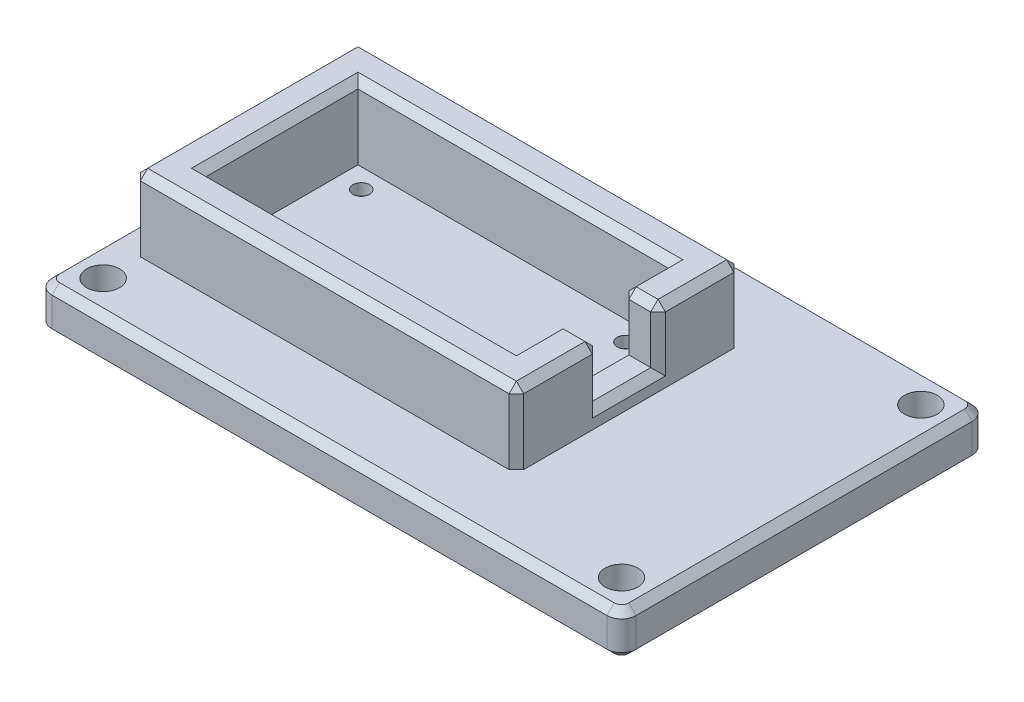
SolidWorks part; units mm, degrees
ref_plane "Front Plane" through (0, 0, 0) normal (0, 0, 1) x (1, 0, 0)
ref_plane "Top Plane" through (0, 0, 0) normal (0, 1, 0) x (1, 0, 0)
ref_plane "Right Plane" through (0, 0, 0) normal (1, 0, 0) x (0, 0, -1)
sketch "Sketch1" plane through (0, 0, 0) normal (0, 1, 0) x (1, 0, 0)
  line L0 (-57.9633, 0) -> (84.3183, 0) construction
  line L1 (-40, 25) -> (40, 25)
  line L2 (-40, 25) -> (-40, -25)
  line L3 (-40, -25) -> (40, -25)
  line L4 (40, 25) -> (40, -25)
  line L5 (-40, 25) -> (40, -25) construction
  line L6 (-40, -25) -> (40, 25) construction
  line L7 (0, 63.2039) -> (0, -51.9764) construction
  dimension "D2" = 50
  dimension "D3" = 80
extrude "Boss-Extrude1" add sketch "Sketch1" along normal blind 6
sketch "Sketch4" plane through (0, 6, 0) normal (0, 1, 0) x (1, 0, 0)
  line L0 (-67.9403, 0) -> (68.6768, 0) construction
  line L2 (-31.5, 10.4) -> (11, 10.4)
  line L3 (-31.5, 10.4) -> (-31.5, -10.4)
  line L4 (-31.5, -10.4) -> (11, -10.4)
  line L5 (11, 10.4) -> (11, -10.4)
  line L6 (-31.5, 10.4) -> (11, -10.4) construction
  line L7 (-31.5, -10.4) -> (11, 10.4) construction
  line L8 (-36.5, 15.4) -> (16, 15.4)
  line L9 (-36.5, 15.4) -> (-36.5, -15.4)
  line L10 (-36.5, -15.4) -> (16, -15.4)
  line L11 (16, 15.4) -> (16, -15.4)
  line L12 (-36.5, 15.4) -> (16, -15.4) construction
  line L13 (-36.5, -15.4) -> (16, 15.4) construction
  point P3 (-10.25, 0)
  point P8 (-10.25, 0)
  dimension "D1" = 11
  dimension "D2" = 5
  dimension "D3" = 5
  dimension "D4" = 20.8
  dimension "D5" = 42.5
extrude "Boss-Extrude2" add sketch "Sketch4" along normal blind 10
sketch "Sketch5" plane through (0, 16, 0) normal (0, 1, 0) x (1, 0, 0)
  line L0 (16, -15.4) -> (16, 15.4) construction
  line L1 (11, 4) -> (16, 4)
  line L2 (11, 4) -> (11, -4)
  line L3 (11, -4) -> (16, -4)
  line L4 (16, 4) -> (16, -4)
  line L5 (11, 4) -> (16, -4) construction
  line L6 (11, -4) -> (16, 4) construction
  line L7 (11, -10.4) -> (11, 10.4) construction
  point P0 (13.5, 0)
  dimension "D1" = 8
extrude "Cut-Extrude1" cut sketch "Sketch5" against normal blind 7.6
sketch "Sketch6" plane through (0, 6, 0) normal (0, 1, 0) x (1, 0, 0)
  line L0 (-10.25, 23.5674) -> (-10.25, -34.9828) construction
  line L1 (-31.5, 10.4) -> (-31.5, -10.4) construction
  line L2 (11, 4) -> (11, -4) construction
  line L3 (-43.8206, 0) -> (24.8562, 0) construction
  circle A0 centre (-28.35, 7.7) radius 1.15
  circle A1 centre (7.85, 7.7) radius 1.15
  circle A2 centre (7.85, -7.7) radius 1.15
  circle A3 centre (-28.35, -7.7) radius 1.15
  dimension "D1" = 2.3
  dimension "D2" = 36.2
  dimension "D3" = 15.4
extrude "Cut-Extrude2" cut sketch "Sketch6" against normal through all
sketch "Sketch7" plane through (0, 0, 0) normal (0, -1, 0) x (1, 0, 0)
  circle A0 centre (-28.35, 7.7) radius 2.1
  circle A1 centre (7.85, 7.7) radius 2.1
  circle A2 centre (-28.35, -7.7) radius 2.1
  circle A3 centre (7.85, -7.7) radius 2.1
  dimension "D1" = 4.2
extrude "Cut-Extrude3" cut sketch "Sketch7" against normal blind 4.41
chamfer "Chamfer3" distance 1 angle 45 26 edges at (-36.5, 11, -15.4) (-36.5, 16, 0) (-36.5, 6, 0) (-36.5, 11, 15.4) (-10.25, 6, 15.4) (16, 11, 15.4) (16, 6, 0) (-10.25, 6, -15.4) (-10.25, 16, -15.4) (16, 11, -15.4) (16, 16, -9.7) (13.5, 16, 4) (11, 12.2, 4) (11, 8.4, 0) (11, 12.2, -4) (11, 16, 7.2) (-10.25, 16, 10.4) (-31.5, 16, 0) (-10.25, 16, -10.4) (11, 16, -7.2) (13.5, 16, -4) (16, 12.2, -4) (16, 8.4, 0) (16, 12.2, 4) (-10.25, 16, 15.4) (16, 16, 9.7)
chamfer "Chamfer4" distance 0.5 angle 45 4 edges at (-28.35, 0, -9.8) (-28.35, 0, 5.6) (7.85, 0, -9.8) (7.85, 0, 5.6)
sketch "Sketch8" plane through (0, 6, 0) normal (0, 1, 0) x (1, 0, 0)
  line L1 (-35.5, 20.5) -> (35.5, 20.5) construction
  line L2 (-35.5, 20.5) -> (-35.5, -20.5) construction
  line L3 (-35.5, -20.5) -> (35.5, -20.5) construction
  line L4 (35.5, 20.5) -> (35.5, -20.5) construction
  line L5 (-35.5, 20.5) -> (35.5, -20.5) construction
  line L6 (-35.5, -20.5) -> (35.5, 20.5) construction
  circle A0 centre (-35.5, 20.5) radius 2.25
  circle A1 centre (35.5, 20.5) radius 2.25
  circle A2 centre (35.5, -20.5) radius 2.25
  circle A3 centre (-35.5, -20.5) radius 2.25
  circle A4 centre (-35.5, -20.5) radius 2.75 construction
  point P0 (0, 0)
  dimension "D3" = 4.5
  dimension "D4" = 5.5
  dimension "D1" = 71
  dimension "D2" = 41
extrude "Cut-Extrude4" cut sketch "Sketch8" against normal through all
fillet "Fillet1" radius 2 4 edges at (-40, 3, -25) (40, 3, -25) (40, 3, 25) (-40, 3, 25)
chamfer "Chamfer5" distance 1 angle 45 16 edges at (39.4142, 0, 24.4142) (40, 0, 0) (0, 0, 25) (-39.4142, 0, 24.4142) (-40, 0, 0) (-39.4142, 0, -24.4142) (0, 0, -25) (39.4142, 0, -24.4142) (39.4142, 6, -24.4142) (40, 6, 0) (39.4142, 6, 24.4142) (0, 6, -25) (-39.4142, 6, -24.4142) (-40, 6, 0) (-39.4142, 6, 24.4142) (0, 6, 25)
